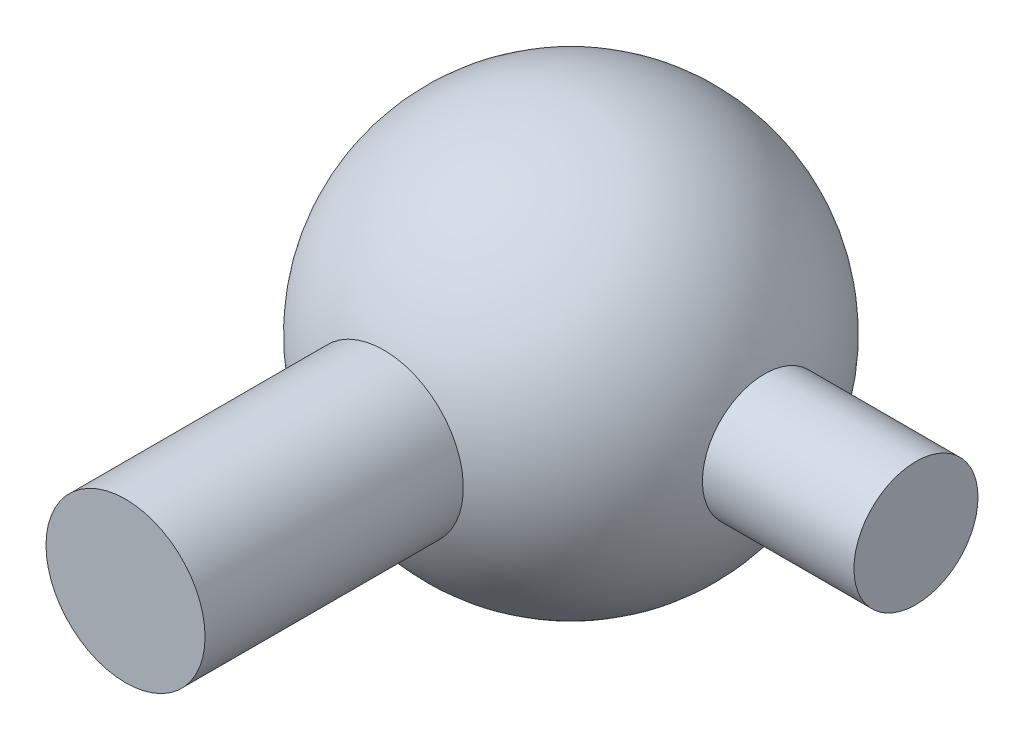
SolidWorks part; units mm, degrees
ref_plane "Plan de face" through (0, 0, 0) normal (0, 0, 1) x (1, 0, 0)
ref_plane "Plan de dessus" through (0, 0, 0) normal (0, 1, 0) x (1, 0, 0)
ref_plane "Plan de droite" through (0, 0, 0) normal (1, 0, 0) x (0, 0, -1)
sketch "Esquisse1" plane through (0, 0, 0) normal (0, 0, 1) x (1, 0, 0)
  line L0 (0, 0) -> (0, 9.6765) construction
  line L1 (0, 6.3899) -> (0, -6.3899)
  arc A0 (0, 6.3899) -> (0, -6.3899) centre (0, 0) ccw
revolve "Révolution3" add sketch "Esquisse1" angle 360 about L0
sketch "Esquisse2" plane through (0, 0, 0) normal (0, 0, 1) x (1, 0, 0)
  circle A0 centre (0, 0) radius 2.5
  dimension "D1" = 5
extrude "Boss.-Extru.1" add sketch "Esquisse2" along normal blind 14
sketch "Esquisse3" plane through (0.8471, 0, 0) normal (1, 0, 0) x (0, 0, -1)
  circle A0 centre (0, 0) radius 1.95
  dimension "D1" = 3.9
extrude "Boss.-Extru.2" add sketch "Esquisse3" along normal blind 10
